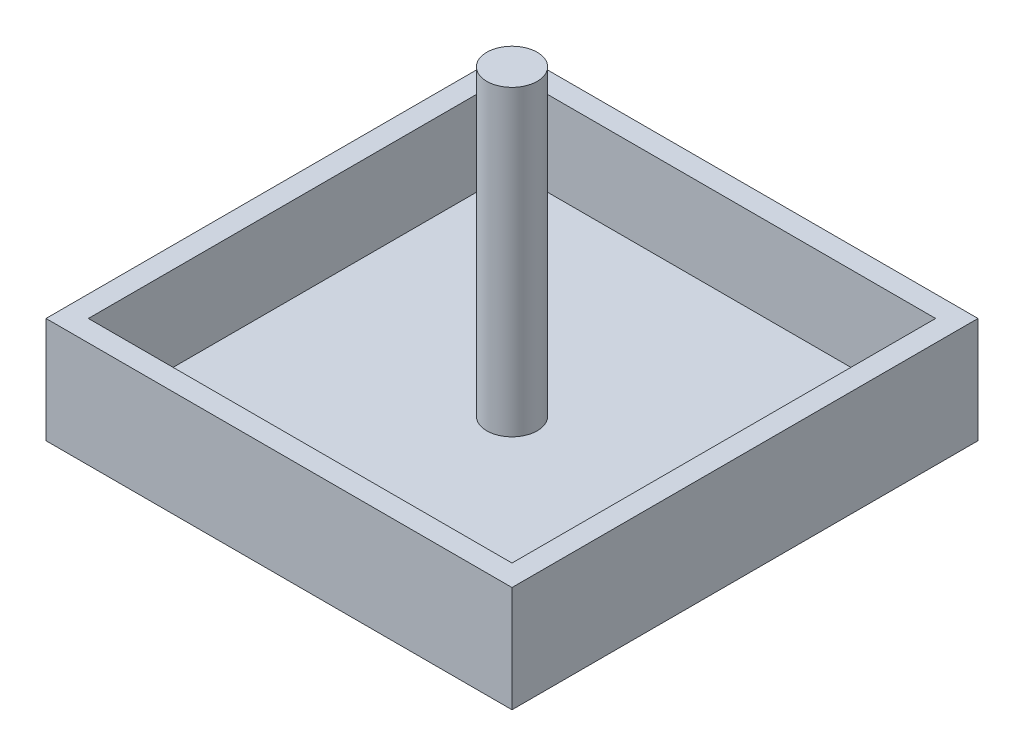
SolidWorks part; units mm, degrees
ref_plane "Plano frontal" through (0, 0, 0) normal (0, 0, 1) x (1, 0, 0)
ref_plane "Plano superior" through (0, 0, 0) normal (0, 1, 0) x (1, 0, 0)
ref_plane "Plano direito" through (0, 0, 0) normal (1, 0, 0) x (0, 0, -1)
sketch "Esboço1" plane through (0, 0, 0) normal (0, 1, 0) x (1, 0, 0)
  line L1 (-35.0121, 4.9879) -> (4.9879, 4.9879)
  line L2 (-35.0121, 4.9879) -> (-35.0121, -35.0121)
  line L3 (-35.0121, -35.0121) -> (4.9879, -35.0121)
  line L4 (4.9879, 4.9879) -> (4.9879, -35.0121)
extrude "Ressalto-extrusão1" add sketch "Esboço1" along normal blind 2
sketch "Esboço2" plane through (0, 0, 0) normal (0, -1, 0) x (1, 0, 0)
  line L0 (-35.0121, 35.0121) -> (-35.0121, -4.9879)
  line L1 (-37.0121, 35.0121) -> (-37.0121, -6.9879)
  line L2 (-35.0121, -4.9879) -> (4.9879, -4.9879)
  line L3 (-35.0121, -6.9879) -> (-37.0121, -6.9879)
  line L4 (-37.0121, -6.9879) -> (6.9879, -6.9879)
  line L5 (4.9879, -4.9879) -> (4.9879, 35.0121)
  line L6 (6.9879, -4.9879) -> (6.9879, -6.9879)
  line L7 (6.9879, -6.9879) -> (6.9879, 37.0121)
  line L8 (4.9879, 35.0121) -> (-35.0121, 35.0121)
  line L9 (4.9879, 37.0121) -> (6.9879, 37.0121)
  line L10 (6.9879, 37.0121) -> (-37.0121, 37.0121)
  line L11 (-37.0121, 35.0121) -> (-37.0121, 37.0121)
  line M3 (-35.0121, 35.0121) -> (-35.0121, -4.9879)
  line M4 (-35.0121, -4.9879) -> (4.9879, -4.9879)
  line M5 (4.9879, -4.9879) -> (4.9879, 35.0121)
  line M6 (4.9879, 35.0121) -> (-35.0121, 35.0121)
extrude "Ressalto-extrusão2" add sketch "Esboço2" against normal blind 10 contours L11 L1 L3 L4 L6 L7 L9 L10 M3 M6 M5 M4
sketch "Esboço3" plane through (0, 2, 0) normal (0, 1, 0) x (1, 0, 0)
  line L0 (4.9879, 4.9879) -> (-35.0121, 4.9879) construction
  line L1 (-35.0121, 4.9879) -> (-35.0121, -35.0121) construction
  circle A0 centre (-15.0121, -15.0121) radius 2.38
  dimension "D1" = 4.76
  dimension "D2" = 20
  dimension "D3" = 20
extrude "Ressalto-extrusão3" add sketch "Esboço3" along normal blind 28.58
